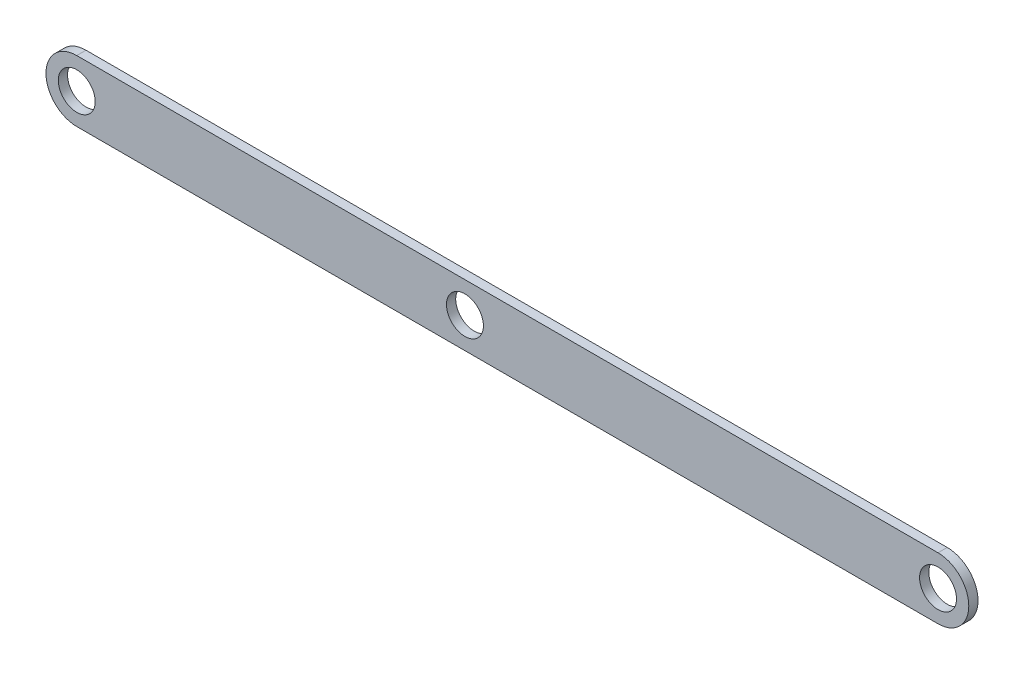
SolidWorks part; units mm, degrees
ref_plane "Front Plane" through (0, 0, 0) normal (0, 0, 1) x (1, 0, 0)
ref_plane "Top Plane" through (0, 0, 0) normal (0, 1, 0) x (1, 0, 0)
ref_plane "Right Plane" through (0, 0, 0) normal (1, 0, 0) x (0, 0, -1)
sketch "Sketch1" plane through (0, 0, 0) normal (0, 0, 1) x (1, 0, 0)
  line L0 (0, 5) -> (140, 5)
  line L6 (0, -5) -> (140, -5)
  arc A2 (0, 5) -> (0, -5) centre (0, 0) ccw
  arc A3 (140, -5) -> (140, 5) centre (140, 0) ccw
  dimension "D1" = 10
  dimension "D2" = 140
extrude "Boss-Extrude1" add sketch "Sketch1" along normal blind 1.5
sketch "Sketch2" plane through (0, 0, 1.5) normal (0, 0, 1) x (1, 0, 0)
  circle A0 centre (0, 0) radius 3
  circle A2 centre (140, 0) radius 3
  circle A3 centre (63.1, 0) radius 3
  dimension "D1" = 6
  dimension "D2" = 140
  dimension "D3" = 76.9
extrude "Cut-Extrude1" cut sketch "Sketch2" against normal through all
